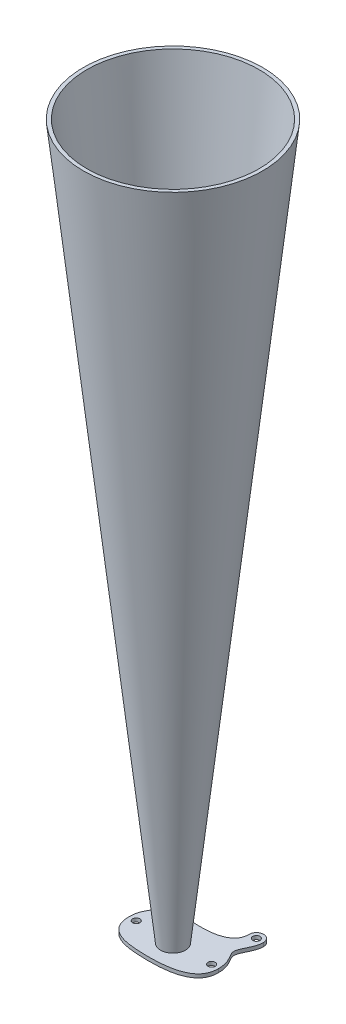
SolidWorks part; units mm, degrees
material "ABS"
ref_plane "Front Plane" through (0, 0, 0) normal (0, 0, 1) x (1, 0, 0)
ref_plane "Top Plane" through (0, 0, 0) normal (0, 1, 0) x (1, 0, 0)
ref_plane "Right Plane" through (0, 0, 0) normal (1, 0, 0) x (0, 0, -1)
sketch "Sketch1" plane through (0, 0, 0) normal (0, 1, 0) x (1, 0, 0)
  circle A1 centre (0, 0) radius 25
  dimension "D2" = 50
extrude "Boss-Extrude1" add sketch "Sketch1" along normal blind 200
sketch "Sketch2" plane through (0, 0, 0) normal (0, 0, 1) x (1, 0, 0)
  line L0 (0, 0) -> (3.35, 0) construction
  line L1 (-25, 0) -> (25, 0) construction
  line L2 (0, 0) -> (-3.35, 0)
  line L3 (0, 0) -> (0, 50000) construction
  line L4 (-25, 200) -> (-3.35, 0)
  line L5 (-3.35, 0) -> (-25, 0)
  line L6 (-25, 0) -> (-25, 200)
  dimension "D1" = 6.7
  dimension "D2" = 3.35
revolve "Cut-Revolve1" cut sketch "Sketch2" angle 360 about L3
shell "Shell1" thickness 1
sketch "Sketch4" plane through (0, 0, 0) normal (0, -1, 0) x (1, 0, 0)
  line L0 (0, 0) -> (0, 50000) construction
  line L1 (0, 0) -> (50000, 0) construction
  line L3 (-0.5, -0.5) -> (0.5, -0.5)
  line L4 (-0.5, -0.5) -> (-0.5, 0.5)
  line L5 (-0.5, 0.5) -> (0.5, 0.5)
  line L6 (0.5, -0.5) -> (0.5, 0.5)
  line L7 (-0.5, -0.5) -> (0.5, 0.5) construction
  line L8 (-0.5, 0.5) -> (0.5, -0.5) construction
  circle A0 centre (0, 0) radius 2.2702 construction
  dimension "D1" = 1
  dimension "D2" = 1
extrude "Boss-Extrude2" add sketch "Sketch4" against normal blind 1 separate body
sketch "Sketch5" plane through (0, 0, 0) normal (0, -1, 0) x (1, 0, 0)
  line L0 (0, 0) -> (0, -50000) construction
  line L1 (-10.5, -12.75) -> (10.5, -12.75) construction
  line L2 (-10.5, -12.75) -> (-10.5, -0.25) construction
  line L3 (-10.5, -0.25) -> (10.5, -0.25) construction
  line L4 (10.5, -0.25) -> (10.5, -12.75) construction
  line L5 (-8.5, 13.4988) -> (-8.5, -38.9988) construction
  line L6 (25.651, -7.75) -> (-25.7304, -7.75) construction
  line L7 (-12.5, 2.0908) -> (-12.5, -27.5908) construction
  line L8 (-12.5, 21.5732) -> (-12.5, -22.0732) construction
  line L9 (-12.5, 38.9378) -> (-12.5, -39.4378) construction
  line L10 (37.3439, 6.75) -> (-38.1954, 6.75) construction
  circle A0 centre (-10.5, -12.75) radius 1
  circle A1 centre (10.5, -12.75) radius 1
  circle A2 centre (-10.5, -0.25) radius 1
  circle A3 centre (10.5, -0.25) radius 1
  arc A4 (-12.5, -12.75) -> (-8.5, -12.75) centre (-10.5, -12.75) ccw
  arc A5 (8.5014, -12.6751) -> (12.5, -12.75) centre (10.5, -12.75) ccw
  circle A6 centre (10.5, -0.25) radius 2 construction
  circle A7 centre (-10.5, -0.25) radius 2 construction
  spline S0 degree 3 poles (-8.5, -12.75) (-8.5, -8.8127) (-0.9123, -6.8957) (8.6119, -8.396) (8.5, -12.75) knots 0 0 0 0 0.45 1 1 1 1
  spline S1 degree 3 poles (-12.5, -0.25) (-12.5, 5.6282) (-1.3381, 7.6289) (12.6582, 6.114) (12.5, -0.25) knots 0 0 0 0 0.45 1 1 1 1
  spline S2 degree 3 poles (-12.5, -12.75) (-12.5, -10.2765) (-8.5, -5.9181) (-12.5, -3.8872) (-12.5, -0.25) knots 0 0 0 0 0.5 1 1 1 1
  spline S3 degree 3 poles (12.5, -12.75) (12.5, -10.2765) (8.5, -5.9181) (12.5, -3.8872) (12.5, -0.25) knots 0 0 0 0 0.5 1 1 1 1
  circle M1 centre (0, 0) radius 3.35
  dimension "D1" = 1
  dimension "D2" = 1
  dimension "D3" = 1
  dimension "D4" = 1
  dimension "D7" = 90
  dimension "D8" = 90
  dimension "D9" = 90
  dimension "D10" = 90
  dimension "D11" = 90
  dimension "D5" = 5
  dimension "D6" = 90
  dimension "D12" = 7
extrude "Boss-Extrude3" add sketch "Sketch5" against normal blind 1 contours A5 S3 S1 S2 A4 S0 A3 A2 A1 A0 M1
